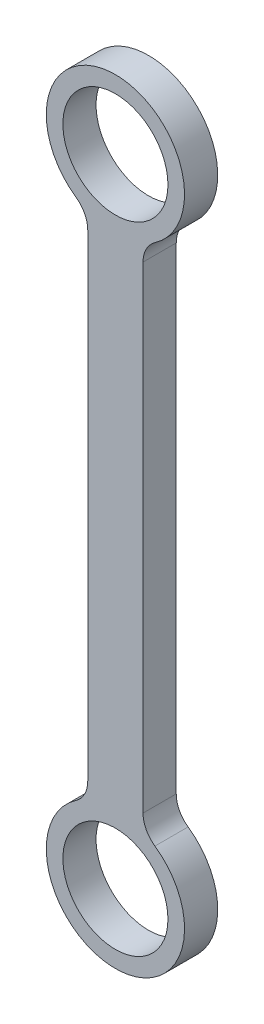
SolidWorks part; units mm, degrees
ref_plane "Alzado" through (0, 0, 0) normal (0, 0, 1) x (1, 0, 0)
ref_plane "Planta" through (0, 0, 0) normal (0, 1, 0) x (1, 0, 0)
ref_plane "Vista lateral" through (0, 0, 0) normal (1, 0, 0) x (0, 0, -1)
sketch "Croquis1" plane through (0, 0, 0) normal (0, 0, 1) x (1, 0, 0)
  line L0 (0, 0) -> (0, 115) construction
  line L2 (5, 0) -> (-5, 0)
  line L3 (5, 0) -> (5, 115)
  line L4 (5, 115) -> (-5, 115)
  line L5 (-5, 0) -> (-5, 115)
  line L6 (5, 0) -> (-5, 115) construction
  line L7 (5, 115) -> (-5, 0) construction
  circle A0 centre (0, 0) radius 12.5
  circle A1 centre (0, 0) radius 9.5
  circle A2 centre (0, 115) radius 12.5
  circle A3 centre (0, 115) radius 9.5
  point P7 (0, 57.5)
  dimension "D1" = 25
  dimension "D2" = 19
  dimension "D3" = 25
  dimension "D4" = 19
  dimension "D5" = 115
  dimension "D6" = 115
  dimension "D7" = 10
extrude "Saliente-Extruir1" add sketch "Croquis1" along normal blind 6 contours A3 L3 A2 L5 | A3 L5 A2 L3 | A2 L5 A0 L3 | A1 L5 A0 L3 | A1 L3 A0 L5
fillet "Redondeo1" radius 5 4 edges at (5, 11.4564, 3) (-5, 11.4564, 3) (-5, 103.5436, 3) (5, 103.5436, 3)
